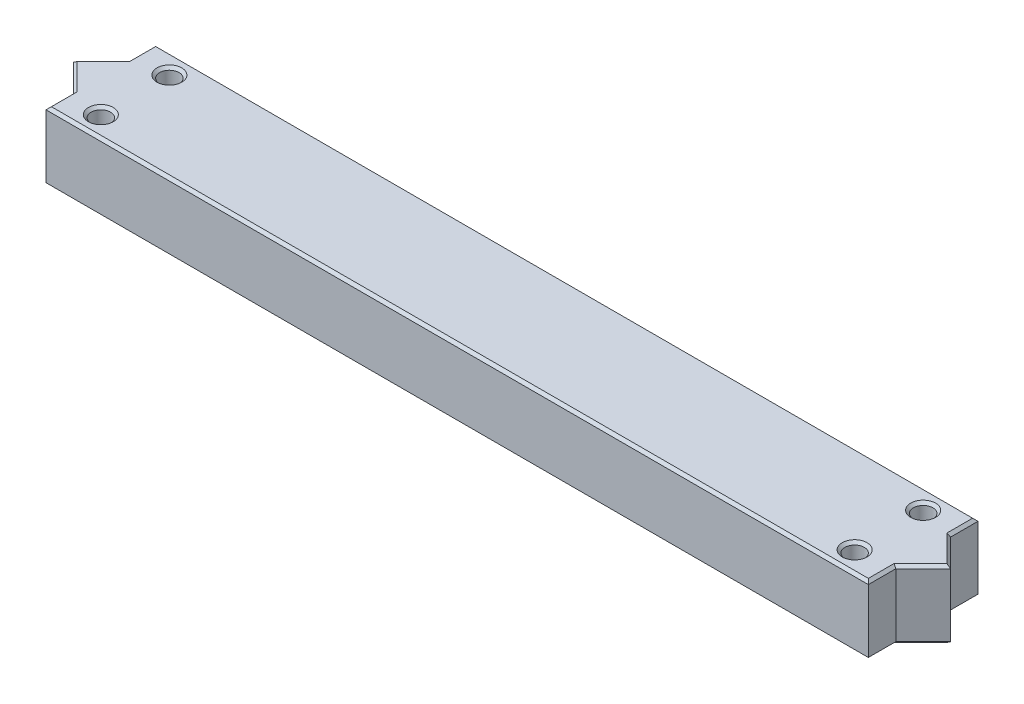
SolidWorks part; units mm, degrees
ref_plane "Front Plane" through (0, 0, 0) normal (0, 0, 1) x (1, 0, 0)
ref_plane "Top Plane" through (0, 0, 0) normal (0, 1, 0) x (1, 0, 0)
ref_plane "Right Plane" through (0, 0, 0) normal (1, 0, 0) x (0, 0, -1)
sketch "Sketch1" plane through (0, 0, 0) normal (0, 1, 0) x (1, 0, 0)
  line L0 (-76.2, 5.08) -> (-81.28, 0)
  line L1 (-76.2, 10.16) -> (76.2, 10.16)
  line L2 (-76.2, 10.16) -> (-76.2, 5.08)
  line L3 (-76.2, -10.16) -> (76.2, -10.16)
  line L4 (76.2, 10.16) -> (76.2, 5.08)
  line L5 (-76.2, 10.16) -> (76.2, -10.16) construction
  line L6 (-76.2, -10.16) -> (76.2, 10.16) construction
  line L7 (-81.28, 0) -> (-76.2, -5.08)
  line L8 (-81.28, 0) -> (-76.2, 0) construction
  line L9 (-76.2, -5.08) -> (-76.2, -10.16)
  line L10 (0, 0) -> (0, 10.16) construction
  line L11 (81.28, 0) -> (76.2, 0) construction
  line L12 (81.28, 0) -> (76.2, -5.08)
  line L13 (76.2, 5.08) -> (81.28, 0)
  line L14 (76.2, -5.08) -> (76.2, -10.16)
  line L15 (-81.28, 0) -> (-58.42, 0) construction
  line L16 (-58.42, 0) -> (-58.42, 10.16) construction
  line L17 (0, 0) -> (76.2, 0) construction
  line L18 (-69.85, 6.35) -> (-69.85, 0) construction
  circle A0 centre (-69.85, 6.35) radius 1.8
  circle A1 centre (-69.85, -6.35) radius 1.8
  circle A2 centre (69.85, -6.35) radius 1.8
  circle A3 centre (69.85, 6.35) radius 1.8
  point P0 (0, 0)
  dimension "D4" = 3.6
  dimension "D1" = 20.32
  dimension "D2" = 152.4
  dimension "D3" = 10.16
  dimension "D5" = 6.35
  dimension "D6" = 22.86
extrude "Boss-Extrude1" add sketch "Sketch1" along normal blind 12.7
chamfer "Chamfer1" distance 0.5 angle 45 28 edges at (69.85, 0, -8.15) (69.85, 0, 8.15) (-69.85, 0, 4.55) (-69.85, 0, -4.55) (78.74, 0, 2.54) (78.74, 0, -2.54) (76.2, 0, -7.62) (0, 0, -10.16) (-76.2, 0, -7.62) (-78.74, 0, -2.54) (-78.74, 0, 2.54) (-76.2, 0, 7.62) (0, 0, 10.16) (76.2, 0, 7.62) (69.85, 12.7, -8.15) (-69.85, 12.7, 4.55) (0, 12.7, 10.16) (-76.2, 12.7, 7.62) (-78.74, 12.7, 2.54) (-78.74, 12.7, -2.54) (-76.2, 12.7, -7.62) (0, 12.7, -10.16) (76.2, 12.7, -7.62) (78.74, 12.7, -2.54) (78.74, 12.7, 2.54) (76.2, 12.7, 7.62) (-69.85, 12.7, -4.55) (69.85, 12.7, 8.15)
